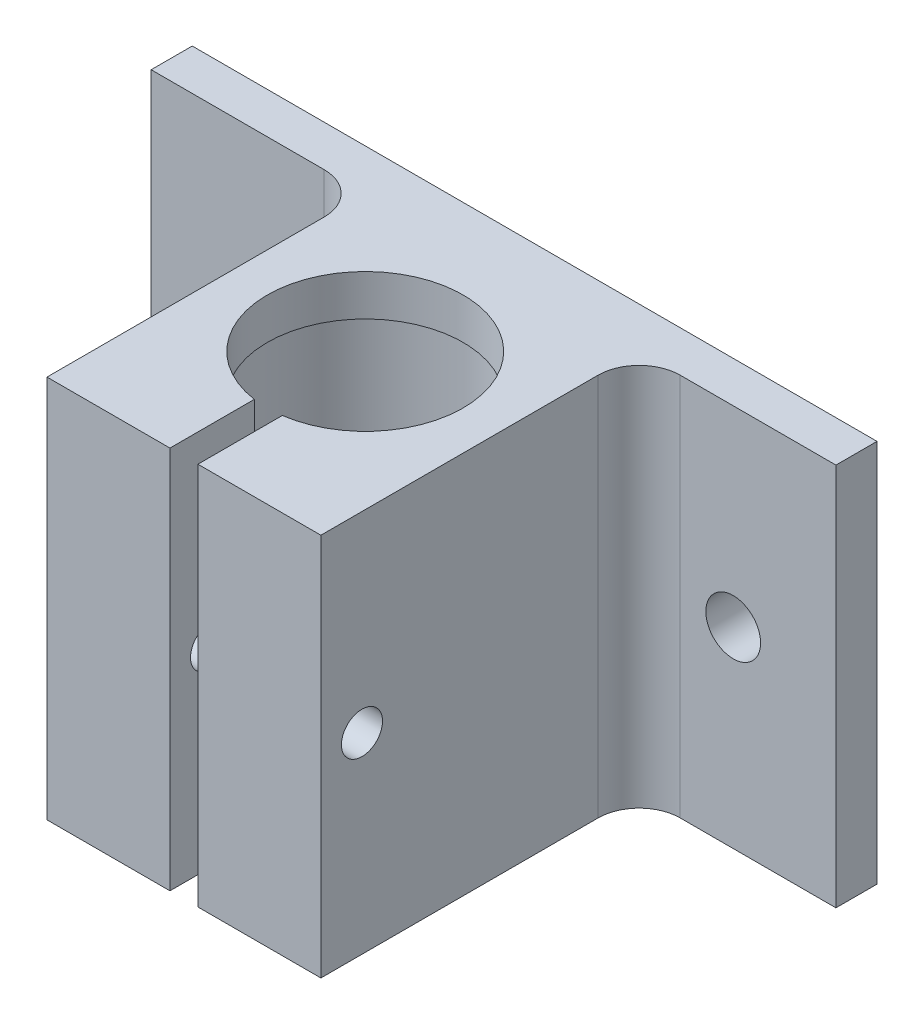
SolidWorks part; units mm, degrees
ref_plane "Front Plane" through (0, 0, 0) normal (0, 0, 1) x (1, 0, 0)
ref_plane "Top Plane" through (0, 0, 0) normal (0, 1, 0) x (1, 0, 0)
ref_plane "Right Plane" through (0, 0, 0) normal (1, 0, 0) x (0, 0, -1)
sketch "Sketch1" plane through (0, 0, 0) normal (0, 1, 0) x (1, 0, 0)
  line L1 (-25.6311, 10) -> (-10, 10)
  line L2 (-25.6311, 10) -> (-25.6311, 13)
  line L3 (-25.6311, 13) -> (24.3689, 13)
  line L4 (24.3689, 10) -> (24.3689, 13)
  line L10 (1.0214, -13.238) -> (10, -13.238)
  line L12 (-10, 10) -> (-10, -13.238)
  line L13 (-10, -13.238) -> (-1.0214, -13.238)
  line L14 (10, 10) -> (10, -13.238)
  line L16 (-1.0214, -13.238) -> (-1.0214, -7.0767)
  line L19 (1.0214, -13.238) -> (1.0214, -7.0767)
  line L20 (10, 10) -> (24.3689, 10)
  arc A0 (1.0214, -7.0767) -> (-1.0214, -7.0767) centre (0, 0) ccw
  point P3 (-0.6311, 16.5)
  dimension "D1" = 14.3
  dimension "D2" = 3
  dimension "D3" = 50
  dimension "D4" = 10
  dimension "D5" = 20
  dimension "D6" = 10
extrude "Boss-Extrude1" add sketch "Sketch1" along normal blind 28
sketch "Sketch2" plane through (-10, 0, 0) normal (-1, 0, 0) x (0, 0, 1)
  line L0 (13.238, 28) -> (13.238, 0) construction
  circle A0 centre (10.238, 14) radius 1.5
  dimension "D1" = 3
  dimension "D2" = 3
extrude "Cut-Extrude1" cut sketch "Sketch2" against normal blind 20
sketch "Sketch3" plane through (-10, 0, 0) normal (-1, 0, 0) x (0, 0, 1)
  line L7 (10.238, 17.1754) -> (7.488, 15.5877)
  line L8 (7.488, 15.5877) -> (7.488, 12.4123)
  line L9 (7.488, 12.4123) -> (10.238, 10.8246)
  line L10 (10.238, 10.8246) -> (12.988, 12.4123)
  line L11 (12.988, 12.4123) -> (12.988, 15.5877)
  line L12 (12.988, 15.5877) -> (10.238, 17.1754)
  circle A0 centre (10.238, 14) radius 2.75 construction
  dimension "D1" = 5.5
extrude "Cut-Extrude2" cut sketch "Sketch3" against normal blind 2
sketch "Sketch4" plane through (0, 0, -13) normal (0, 0, -1) x (-1, 0, 0)
  line L0 (0, 0) -> (0, 34.3534) construction
  line L1 (-24.3689, 14) -> (30.6657, 14) construction
  line L2 (-24.3689, 28) -> (-24.3689, 0) construction
  circle A0 centre (-16.8689, 14) radius 2
  circle A1 centre (16.8689, 14) radius 2
  dimension "D1" = 4
  dimension "D2" = 7.5
extrude "Cut-Extrude3" cut sketch "Sketch4" against normal blind 3
fillet "Fillet1" radius 3 1 edges at (10, 14, -10)
fillet "Fillet2" radius 3 1 edges at (-10, 14, -10)
sketch "Sketch5" plane through (0, 0, 0) normal (0, -1, 0) x (1, 0, 0)
  circle A0 centre (0, 0) radius 7.75
  dimension "D1" = 15.5
extrude "Cut-Extrude4" cut sketch "Sketch5" against normal blind 25
sketch "Sketch6" plane through (0, 0, -13) normal (0, 0, -1) x (-1, 0, 0)
  line L1 (-24.3689, 28) -> (25.6311, 28)
  line L2 (-24.3689, 28) -> (-24.3689, 0)
  line L3 (-24.3689, 0) -> (25.6311, 0)
  line L4 (25.6311, 28) -> (25.6311, 0)
  circle A0 centre (-16.8689, 14) radius 2
  circle A1 centre (16.8689, 14) radius 2
